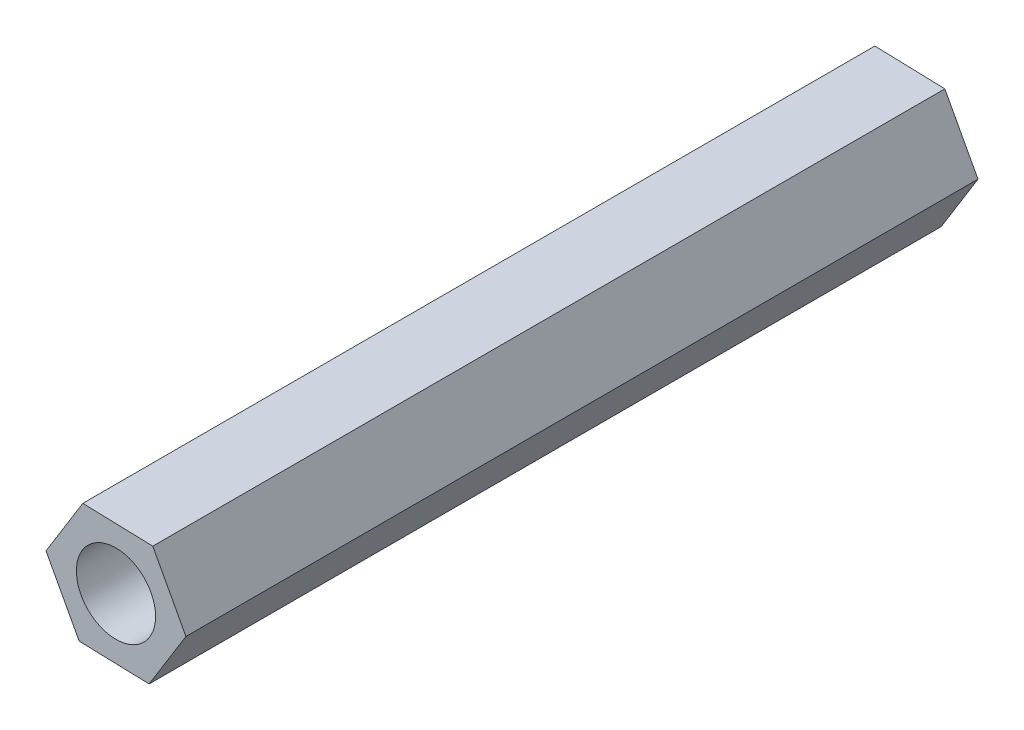
SolidWorks part; units mm, degrees
ref_plane "Front Plane" through (0, 0, 0) normal (0, 0, 1) x (1, 0, 0)
ref_plane "Top Plane" through (0, 0, 0) normal (0, 1, 0) x (1, 0, 0)
ref_plane "Right Plane" through (0, 0, 0) normal (1, 0, 0) x (0, 0, -1)
sketch "Sketch1" plane through (0, 0, 0) normal (0, 0, 1) x (1, 0, 0)
  line L1 (1.256, -2.3348) -> (2.65, -0.0797)
  line L2 (2.65, -0.0797) -> (1.394, 2.2551)
  line L3 (1.394, 2.2551) -> (-1.256, 2.3348)
  line L4 (-1.256, 2.3348) -> (-2.65, 0.0797)
  line L5 (-2.65, 0.0797) -> (-1.394, -2.2551)
  line L6 (-1.394, -2.2551) -> (1.256, -2.3348)
  circle A0 centre (0, 0) radius 2.296 construction
  circle A1 centre (0, 0) radius 1.5
  dimension "D2" = 3
  dimension "D1" = 5.3
extrude "Boss-Extrude1" add sketch "Sketch1" along normal blind 30
